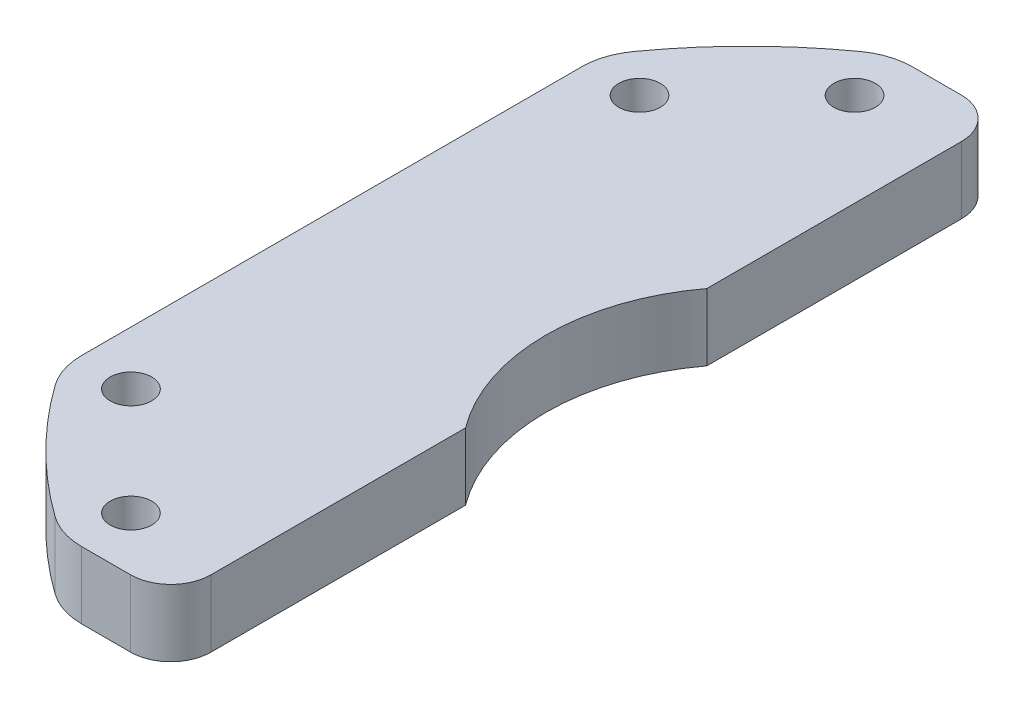
SolidWorks part; units mm, degrees
material "6061 合金"
ref_plane "前视基准面" through (0, 0, 0) normal (0, 0, 1) x (1, 0, 0)
ref_plane "上视基准面" through (0, 0, 0) normal (0, 1, 0) x (1, 0, 0)
ref_plane "右视基准面" through (0, 0, 0) normal (1, 0, 0) x (0, 0, -1)
sketch "草图1" plane through (0, 0, 0) normal (0, 1, 0) x (1, 0, 0)
  line L0 (-20.199, 31) -> (20.199, 31)
  line L1 (-31, 20.199) -> (-31, -20.199)
  line L2 (-20.199, -31) -> (20.199, -31)
  line L3 (31, 20.199) -> (31, -20.199)
  arc A24 (-20.199, 31) -> (-31, 20.199) centre (0, 0) ccw
  arc A25 (31, 20.199) -> (20.199, 31) centre (0, 0) ccw
  arc A26 (20.199, -31) -> (31, -20.199) centre (0, 0) ccw
  arc A27 (-31, -20.199) -> (-20.199, -31) centre (0, 0) ccw
  dimension "D1" = 74
  dimension "D2" = 31
  dimension "D3" = 31
  dimension "D4" = 31
  dimension "D5" = 31
extrude "凸台-拉伸1" add sketch "草图1" along normal blind 5
sketch "草图2" plane through (0, 5, 0) normal (0, 1, 0) x (1, 0, 0)
  circle A0 centre (0, 0) radius 15
  dimension "D1" = 30
extrude "切除-拉伸1" cut sketch "草图2" against normal blind 10
sketch "草图3" plane through (0, 5, 0) normal (0, 1, 0) x (1, 0, 0)
  line L0 (-26.9989, 18.9752) -> (0, 0) construction
  line L1 (0, 0) -> (-33, 0) construction
  line L2 (0, 0) -> (-23.3345, 23.3345) construction
  line L3 (0, 33) -> (0, 0) construction
  circle A0 centre (0, 0) radius 33 construction
  circle A1 centre (-26.9989, 18.9752) radius 1.55
  circle A2 centre (-18.9752, 26.9989) radius 1.55
  circle A3 centre (26.9989, 18.9752) radius 1.55
  circle A4 centre (18.9752, 26.9989) radius 1.55
  circle A5 centre (26.9989, -18.9752) radius 1.55
  circle A6 centre (18.9752, -26.9989) radius 1.55
  circle A7 centre (-26.9989, -18.9752) radius 1.55
  circle A8 centre (-18.9752, -26.9989) radius 1.55
  dimension "D1" = 66
  dimension "D3" = 3.1
  dimension "D2" = 35.1
  dimension "D4" = 45
extrude "切除-拉伸2" cut sketch "草图3" against normal blind 10
sketch "草图4" plane through (0, 5, 0) normal (0, 1, 0) x (1, 0, 0)
  circle B0 centre (18.6877, 26.5899) radius 1.55
  circle B1 centre (26.5899, 18.6877) radius 1.55
  circle B2 centre (26.5899, -18.6877) radius 1.55
  circle B3 centre (18.6877, -26.5899) radius 1.55
  circle B4 centre (-18.6877, -26.5899) radius 1.55
  circle B5 centre (-26.5899, -18.6877) radius 1.55
  circle B6 centre (-26.5899, 18.6877) radius 1.55
  circle B7 centre (-18.6877, 26.5899) radius 1.55
  arc B8 (-29.742, 3.9261) -> (-29.742, -3.9261) centre (0, 0) ccw
  arc B9 (-29.9601, -18.4937) -> (-29.742, -3.9261) centre (-79.312, -10.4695) ccw
  arc B10 (-29.9601, -18.4937) -> (-29.4534, -20.7002) centre (-26.9989, -18.9752) ccw
  arc B11 (-29.4534, -20.7002) -> (-20.7002, -29.4534) centre (0, 0) ccw
  arc B12 (-20.7002, -29.4534) -> (-18.4937, -29.9601) centre (-18.9752, -26.9989) ccw
  arc B13 (-3.9261, -29.742) -> (-18.4937, -29.9601) centre (-10.4695, -79.312) ccw
  arc B14 (-3.9261, -29.742) -> (3.9261, -29.742) centre (0, 0) ccw
  arc B15 (18.4937, -29.9601) -> (3.9261, -29.742) centre (10.4695, -79.312) ccw
  arc B16 (18.4937, -29.9601) -> (20.7002, -29.4534) centre (18.9752, -26.9989) ccw
  arc B17 (20.7002, -29.4534) -> (29.4534, -20.7002) centre (0, 0) ccw
  arc B18 (29.4534, -20.7002) -> (29.9601, -18.4937) centre (26.9989, -18.9752) ccw
  arc B19 (29.742, -3.9261) -> (29.9601, -18.4937) centre (79.312, -10.4695) ccw
  arc B20 (29.742, -3.9261) -> (29.742, 3.9261) centre (0, 0) ccw
  arc B21 (29.9601, 18.4937) -> (29.742, 3.9261) centre (79.312, 10.4695) ccw
  arc B22 (29.9601, 18.4937) -> (29.4534, 20.7002) centre (26.9989, 18.9752) ccw
  arc B23 (29.4534, 20.7002) -> (20.7002, 29.4534) centre (0, 0) ccw
  arc B24 (20.7002, 29.4534) -> (18.4937, 29.9601) centre (18.9752, 26.9989) ccw
  arc B25 (3.9261, 29.742) -> (18.4937, 29.9601) centre (10.4695, 79.312) ccw
  arc B26 (3.9261, 29.742) -> (-3.9261, 29.742) centre (0, 0) ccw
  arc B27 (-18.4937, 29.9601) -> (-3.9261, 29.742) centre (-10.4695, 79.312) ccw
  arc B28 (-18.4937, 29.9601) -> (-20.7002, 29.4534) centre (-18.9752, 26.9989) ccw
  arc B29 (-20.7002, 29.4534) -> (-29.4534, 20.7002) centre (0, 0) ccw
  arc B30 (-29.4534, 20.7002) -> (-29.9601, 18.4937) centre (-26.9989, 18.9752) ccw
  arc B31 (-29.742, 3.9261) -> (-29.9601, 18.4937) centre (-79.312, 10.4695) ccw
sketch_block_instance "块2-1"
sketch_block "块2"
sketch "草图7" plane through (0, 5, 0) normal (0, 1, 0) x (1, 0, 0)
  line L0 (0, 0) -> (0, 31) construction
  line L1 (0, 0) -> (31, 0) construction
  line L2 (-12, 48.931) -> (37.1082, 48.931)
  line L3 (-12, 48.931) -> (-12, -35.9913)
  line L4 (-12, -35.9913) -> (37.1082, -35.9913)
  line L5 (37.1082, 48.931) -> (37.1082, -35.9913)
  line L6 (20.199, 31) -> (-20.199, 31) construction
  line L7 (31, -20.199) -> (31, 20.199) construction
  dimension "D1" = 12
extrude "切除-拉伸4" cut sketch "草图7" against normal blind 10
fillet "圆角1" radius 3 2 edges at (-12, 2.5, 31) (-12, 2.5, -31)
fillet "圆角2" radius 5 4 edges at (-20.199, 2.5, 31) (-31, 2.5, 20.199) (-31, 2.5, -20.199) (-20.199, 2.5, -31)
